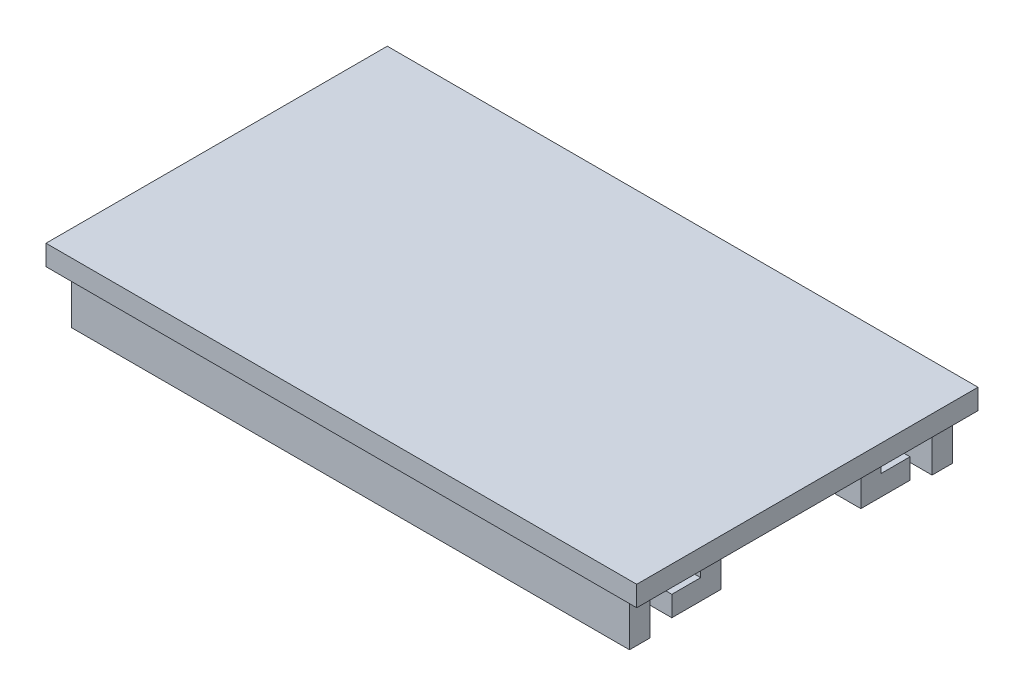
SolidWorks part; units mm, degrees
material "Acrylic (Medium-high impact)"
ref_plane "Front Plane" through (0, 0, 0) normal (0, 0, 1) x (1, 0, 0)
ref_plane "Top Plane" through (0, 0, 0) normal (0, 1, 0) x (1, 0, 0)
ref_plane "Right Plane" through (0, 0, 0) normal (1, 0, 0) x (0, 0, -1)
sketch "Sketch1" plane through (0, 0, 0) normal (0, 1, 0) x (1, 0, 0)
  line L0 (0, 52) -> (0, -52) construction
  line L1 (-90, 52) -> (90, 52)
  line L2 (-90, 52) -> (-90, -52)
  line L3 (-90, -52) -> (90, -52)
  line L4 (90, 52) -> (90, -52)
  line L5 (-90, 0) -> (90, 0) construction
  point P8 (0, 0)
  dimension "D1" = 180
  dimension "D2" = 104
extrude "Boss-Extrude1" add sketch "Sketch1" along normal blind 6.2
ref_plane "Plane1" through (90, 0, 0) normal (-1, 0, 0) x (0, 0, 1)
sketch "Sketch3" plane through (90, 0, 0) normal (-1, 0, 0) x (0, 0, 1)
  line L0 (49.2, 0) -> (49.2, -15)
  line L1 (49.2, -15) -> (43, -15)
  line L2 (43, -15) -> (43, 0)
  line L3 (43, 0) -> (49.2, 0)
  line L4 (27.5, 0) -> (21.3, 0)
  line L5 (21.3, 0) -> (21.3, -13)
  line L6 (21.3, -13) -> (36.3, -13)
  line L7 (36.3, -13) -> (36.3, -6.8)
  line L8 (36.3, -6.8) -> (27.5, -6.8)
  line L9 (27.5, -6.8) -> (27.5, 0)
  line L10 (0, 0) -> (0, -30.7177) construction
  line L11 (-27.5, -6.8) -> (-27.5, 0)
  line L12 (-36.3, -6.8) -> (-27.5, -6.8)
  line L13 (-36.3, -13) -> (-36.3, -6.8)
  line L14 (-21.3, -13) -> (-36.3, -13)
  line L15 (-52, 0) -> (52, 0)
  line L16 (-52, 6.2) -> (-52, 0)
  line L17 (52, 6.2) -> (-52, 6.2)
  line L18 (52, 0) -> (52, 6.2)
  line L19 (-52, 0) -> (52, 0)
  line L20 (-52, 6.2) -> (-52, 0)
  line L21 (52, 6.2) -> (-52, 6.2)
  line L22 (52, 0) -> (52, 6.2)
  line L23 (-21.3, 0) -> (-21.3, -13)
  line L24 (-27.5, 0) -> (-21.3, 0)
  line L25 (-43, 0) -> (-49.2, 0)
  line L26 (-43, -15) -> (-43, 0)
  line L27 (-49.2, -15) -> (-43, -15)
  line L28 (-49.2, 0) -> (-49.2, -15)
  dimension "D1" = 6.2
  dimension "D2" = 6.8
  dimension "D3" = 15.5
  dimension "D4" = 6.7
  dimension "D5" = 6.2
  dimension "D6" = 15
  dimension "D7" = 0
  dimension "D8" = 86
  dimension "D9" = 15
  dimension "D10" = 13
  dimension "D11" = 8.8
extrude "Boss-Extrude2" add sketch "Sketch3" along normal offset from surface (170 mm away) 5 from offset 5 contours L3 L2 L1 L0 | L8 L9 L4 L5 L6 L7 | L23 L19 L11 L12 L13 L14 | L19 L28 L27 L26 up to face at (-90, 3.1, 0)
